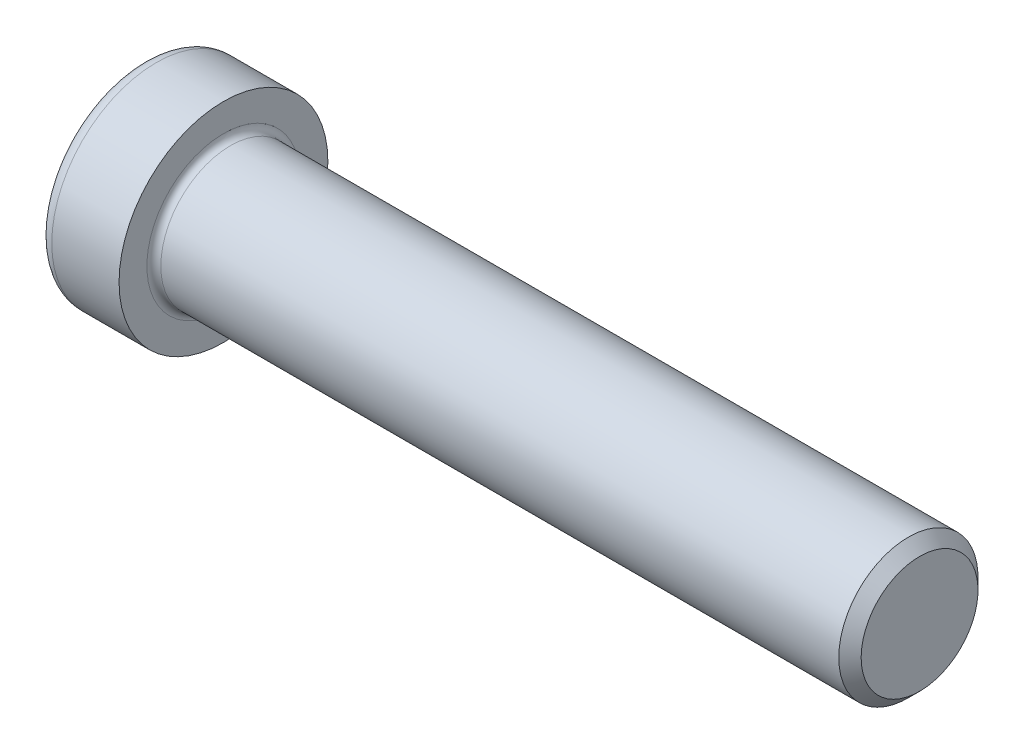
SolidWorks part; units mm, degrees
revolve "Base-Revolve" add sketch "BodySke"
sketch "BodySke" plane through (0, 0, 0) normal (0, 0, 1) x (1, 0, 0)
  line L0 (0, 0) -> (0, 9)
  line L1 (0, 9) -> (7, 9)
  line L2 (7, 9) -> (7, 6)
  line L3 (7, 6) -> (66.036, 6)
  line L4 (67, 5.036) -> (67, 0)
  line L5 (67, 0) -> (0, 0)
  line L6 (-31.75, 0) -> (127, 0) construction
  line L8 (67, 5.036) -> (66.036, 6)
  line L10 (67, -5.036) -> (66.036, -6) construction
  line L11 (8.75, 4.525) -> (8.75, -1.825) construction
  line L12 (37, 4.525) -> (37, -1.825) construction
  line L13 (7, 4.525) -> (7, -1.825) construction
  dimension "Head_ht" = 7
  dimension "Length" = 60
  dimension "Body_ch_ang" = 45
  dimension "Diameter" = 12
  dimension "Minor_dia" = 10.072
  dimension "Advance" = 1.75
  dimension "Thread_nom" = 30
  dimension "Thread_length" = 60
  dimension "Head_dia" = 18
cosmetic thread "ThreadCosmetic"
fillet "Fillet1" radius 0.6 1 edges at (7, 0, 6)
fillet "Fillet2" radius 1.2 1 edges at (0, 0, 9)
material "AISI 316 Нержавеющая сталь, лист (SS)"
ref_plane "Plane1" through (0, 0, 0) normal (0, 0, 1) x (1, 0, 0)
ref_plane "Plane2" through (0, 0, 0) normal (0, 1, 0) x (1, 0, 0)
ref_plane "Plane3" through (0, 0, 0) normal (1, 0, 0) x (0, 0, -1)
other "Configuration Table"
sketch "Sketch2" plane through (0, 0, 0) normal (0, 0, 1) x (1, 0, 0)
  line L0 (0, 4) -> (5, 4)
  line L1 (5, 4) -> (7.3094, 0)
  line L2 (-31.75, 0) -> (127, 0) construction
  line L3 (7.3094, 0) -> (0, 0)
  line L4 (0, 0) -> (0, 4)
  line L6 (0, 0) -> (47.625, 0) construction
  dimension "D1" = 4
  dimension "D2" = 60
  dimension "Depth" = 5
revolve "Hex-PreBroach" cut sketch "Sketch2" angle 360 about L6
sketch "Sketch3" plane through (0, 0, 0) normal (-1, 0, 0) x (0, 0.5, 0.866)
  line L0 (2.3094, 4) -> (-2.3094, 4)
  line L1 (-2.3094, 4) -> (-4.6188, 0)
  line L2 (2.3094, 4) -> (4.6188, 0)
  line L3 (2.3094, -4) -> (4.6188, 0)
  line L4 (2.3094, -4) -> (-2.3094, -4)
  line L5 (-2.3094, -4) -> (-4.6188, 0)
  dimension "D1" = 4
  dimension "D2" = 4
  dimension "Hex_size" = 8
extrude "Hex" cut sketch "Sketch3" against normal blind 5
sketch "ThdSchSke" plane through (0, 0, 0) normal (0, 0, 1) x (1, 0, 0)
  line L0 (37, -5.036) -> (36.325, -6)
  line L1 (37, -5.036) -> (37.675, -6)
  line L2 (37.675, -6) -> (37.675, -7.5)
  line L3 (-3.175, 0) -> (5.1513, 0) construction
  line L4 (0, 7.8) -> (0, -7.8) construction
  line L5 (37.675, -7.5) -> (36.325, -7.5)
  line L6 (36.325, -7.5) -> (36.325, -6)
  dimension "Thread_minor" = 10.072
  dimension "Diameter" = 12
  dimension "Start" = 37
revolve "ThreadSchematic" [suppressed] cut sketch "ThdSchSke" angle 360 about L3
pattern_linear "ThdSchPat" [suppressed]
equation "\"D2@Sketch3\" = \"Hex_size@Sketch3\" / 2"
equation "\"D1@Sketch3\" = \"Hex_size@Sketch3\" / 2"
equation "\"D1@Sketch2\" = \"Hex_size@Sketch3\" / 2"
equation "\"Thread_minor@ThreadCosmetic\"  =  \"Minor_dia@BodySke\""
equation "\"Depth@Sketch2\" =  \"Key_eng@Hex\""
equation "\"Thread_length@ThreadCosmetic\" = ((sgn( (\"Length@BodySke\" - \"Advance@BodySke\" * 3.0) - \"Thread_nom@BodySke\" )-1)*( (\"Length@BodySke\" - \"Advance@BodySke\" * 3.0) - \"Thread_nom@BodySke\" ))/-2+ \"Thread_nom@BodySke\""
equation "\"Thread_minor@ThdSchSke\" = \"Minor_dia@BodySke\""
equation "\"Diameter@ThdSchSke\" = \"Diameter@BodySke\""
equation "\"Overcut@ThdSchSke\" = \"Diameter@BodySke\" * 1.25"
equation "\"Start@ThdSchSke\" = \"Head_ht@BodySke\" + \"Length@BodySke\" - \"Thread_length@ThreadCosmetic\"  '---Non-countersunk---"
equation "\"Num_threads@ThdSchPat\" = int( \"Thread_length@ThreadCosmetic\" / \"Advance@BodySke\" + 0.999 )  + 1"
equation "\"Advance@ThdSchPat\" = \"Thread_length@ThreadCosmetic\" /  (\"Num_threads@ThdSchPat\" - 1) 'relax it"
equation "\"Num_threads@ThdSchPat\" = \"Num_threads@ThdSchPat\" - sgn( \"Num_threads@ThdSchPat\" - 1) '---chamfered tips only---"
